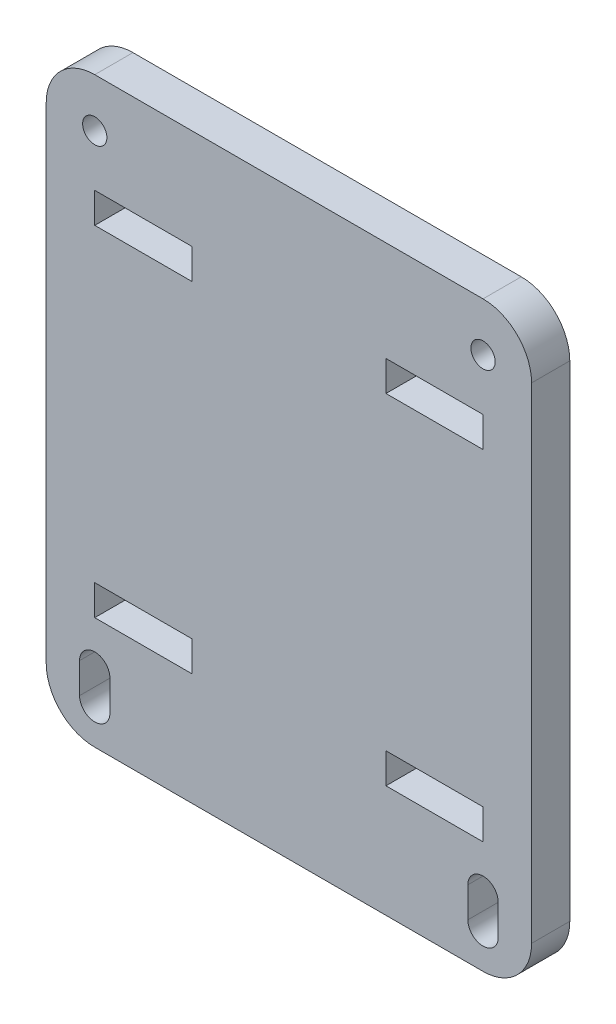
SolidWorks part; units mm, degrees
ref_plane "Front Plane" through (0, 0, 0) normal (0, 0, 1) x (1, 0, 0)
ref_plane "Top Plane" through (0, 0, 0) normal (0, 1, 0) x (1, 0, 0)
ref_plane "Right Plane" through (0, 0, 0) normal (1, 0, 0) x (0, 0, -1)
sketch "Sketch1" plane through (0, 0, 0) normal (0, 0, 1) x (1, 0, 0)
  line L1 (-127, 152.4) -> (0, 152.4)
  line L2 (-127, 152.4) -> (-127, 0)
  line L3 (-127, 0) -> (0, 0)
  line L4 (0, 152.4) -> (0, 0)
  dimension "D1" = 152.4
  dimension "D2" = 127
extrude "Boss-Extrude1" add sketch "Sketch1" along normal blind 10
sketch "Sketch2" plane through (0, 0, 10) normal (0, 0, 1) x (1, 0, 0)
  line L0 (0, 152.4) -> (-127, 152.4) construction
  line L1 (-114.3, 126.1923) -> (-88.9, 126.1923)
  line L2 (-114.3, 126.1923) -> (-114.3, 118.2548)
  line L3 (-114.3, 118.2548) -> (-88.9, 118.2548)
  line L4 (-88.9, 126.1923) -> (-88.9, 118.2548)
  line L5 (-127, 152.4) -> (-127, 0) construction
  dimension "D1" = 26.2077
  dimension "D2" = 12.7
  dimension "D3" = 7.9375
  dimension "D4" = 25.4
extrude "Cut-Extrude1" cut sketch "Sketch2" against normal blind 10
pattern_linear "LPattern1" count 2 spacing 76.2 along (1, 0, 0) count 2 spacing 88.9 along (0, -1, 0) of "Cut-Extrude1"
sketch "Sketch3" plane through (0, 0, 10) normal (0, 0, 1) x (1, 0, 0)
  line L0 (0, 152.4) -> (-127, 152.4) construction
  line L1 (-127, 152.4) -> (-127, 0) construction
  circle A0 centre (-114.3, 139.7) radius 3.175
  dimension "D3" = 6.35
  dimension "D1" = 12.7
  dimension "D2" = 12.7
extrude "Cut-Extrude2" cut sketch "Sketch3" against normal blind 10
pattern_linear "LPattern2" count 2 spacing 101.6 along (1, 0, 0) of "Cut-Extrude2"
sketch "Sketch4" plane through (0, 0, 10) normal (0, 0, 1) x (1, 0, 0)
  line L0 (-114.3, 17.6403) -> (-114.3, 9.7028) construction
  line L1 (-110.33, 17.6403) -> (-110.33, 9.7028)
  line L2 (-118.27, 17.6403) -> (-118.27, 9.7028)
  line L3 (-127, 0) -> (0, 0) construction
  line L4 (-127, 152.4) -> (-127, 0) construction
  arc A0 (-110.33, 17.6403) -> (-118.27, 17.6403) centre (-114.3, 17.6403) ccw
  arc A1 (-118.27, 9.7028) -> (-110.33, 9.7028) centre (-114.3, 9.7028) ccw
  point P2 (-114.3, 13.6715)
  dimension "D1" = 3.97
  dimension "D2" = 9.7028
  dimension "D3" = 12.7
  dimension "D4" = 7.9375
extrude "Cut-Extrude3" cut sketch "Sketch4" against normal blind 10
pattern_linear "LPattern3" count 2 spacing 101.6 along (1, 0, 0) of "Cut-Extrude3"
fillet "Fillet1" radius 12.7 1 edges at (0, 152.4, 5)
fillet "Fillet2" radius 12.7 3 edges at (0, 0, 5) (-127, 0, 5) (-127, 152.4, 5)
